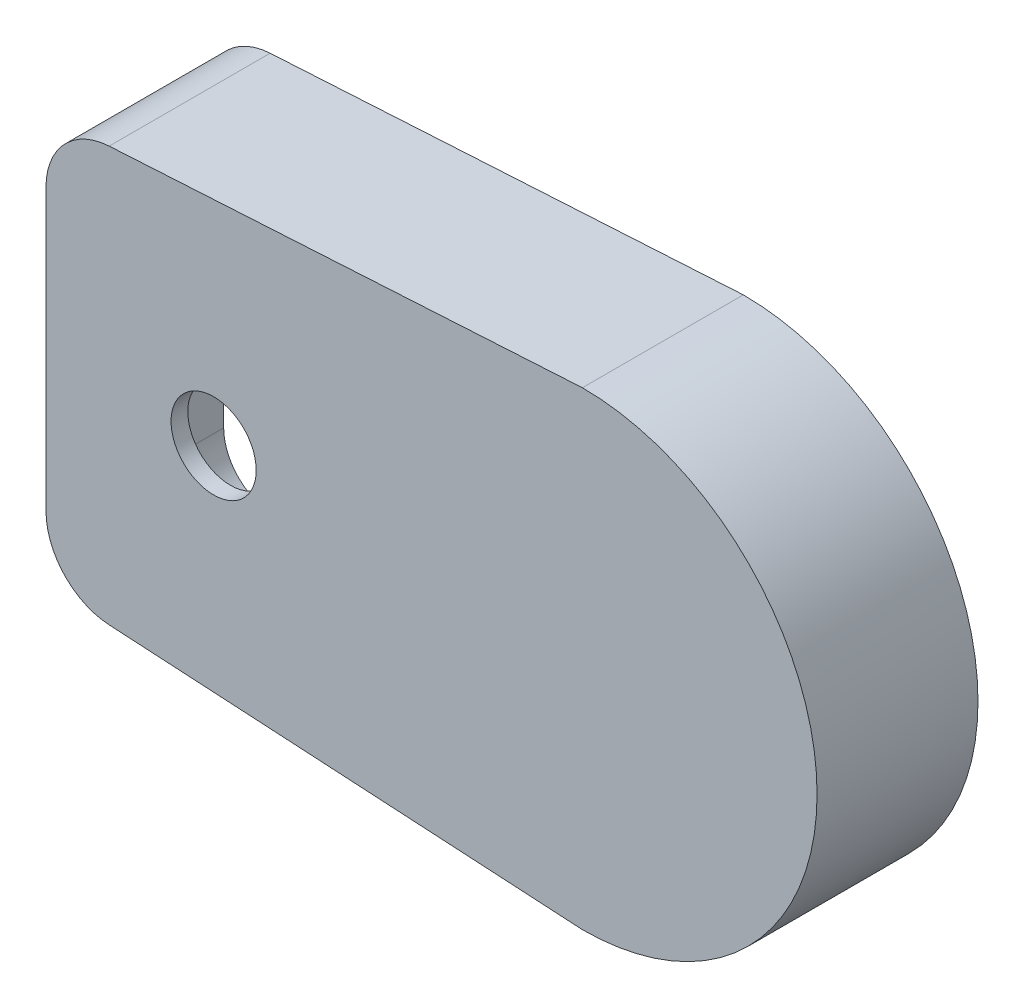
SolidWorks part; units mm, degrees
ref_plane "Front Plane" through (0, 0, 0) normal (0, 0, 1) x (1, 0, 0)
ref_plane "Top Plane" through (0, 0, 0) normal (0, 1, 0) x (1, 0, 0)
ref_plane "Right Plane" through (0, 0, 0) normal (1, 0, 0) x (0, 0, -1)
sketch "Sketch1" plane through (0, 0, 0) normal (0, 0, 1) x (1, 0, 0)
  line L0 (0, 0) -> (230, 0) construction
  line L1 (160, 52.3684) -> (160, -88.6842) construction
  line L2 (0, 41.8729) -> (0, -41.8729)
  line L3 (18.8457, 61.8395) -> (160, 70)
  line L4 (18.8457, -61.8395) -> (160, -70)
  arc A0 (160, -70) -> (160, 70) centre (160, 0) ccw
  arc A1 (18.8457, 61.8395) -> (0, 41.8729) centre (20, 41.8729) ccw
  arc A2 (18.8457, -61.8395) -> (0, -41.8729) centre (20, -41.8729) cw
  point P12 (0, 60.75)
  point P15 (0, -60.75)
  dimension "D4" = 20
  dimension "D5" = 20
  dimension "D1" = 230
  dimension "D2" = 70
  dimension "D3" = 121.5
extrude "Boss-Extrude1" add sketch "Sketch1" along normal mid plane 48 contours L3 A0 L4 A2 L2 A1
sketch "Sketch2" plane through (0, 0, -24) normal (0, 0, -1) x (-1, 0, 0)
  line L6 (-19.1343, 56.8479) -> (-160.1417, 64.9998)
  line L7 (-160.1417, -64.9998) -> (-19.1343, -56.8479)
  line L8 (-5, -41.8729) -> (-5, 41.8729)
  line L9 (-19.1343, 56.8479) -> (-160.1417, 64.9998)
  line L10 (-160.1417, -64.9998) -> (-19.1343, -56.8479)
  line L11 (-5, -41.8729) -> (-5, 41.8729)
  arc A6 (-5, 41.8729) -> (-19.1343, 56.8479) centre (-20, 41.8729) ccw
  arc A7 (-160.1417, 64.9998) -> (-160.1417, -64.9998) centre (-160, 0) ccw
  arc A8 (-19.1343, -56.8479) -> (-5, -41.8729) centre (-20, -41.8729) ccw
  arc A9 (-5, 41.8729) -> (-19.1343, 56.8479) centre (-20, 41.8729) ccw
  arc A10 (-160.1417, 64.9998) -> (-160.1417, -64.9998) centre (-160, 0) ccw
  arc A11 (-19.1343, -56.8479) -> (-5, -41.8729) centre (-20, -41.8729) ccw
  dimension "D1" = 5
extrude "Cut-Extrude1" cut sketch "Sketch2" against normal blind 43
sketch "Sketch7" plane through (0, 0, 24) normal (0, 0, 1) x (1, 0, 0)
  circle A0 centre (50, 0) radius 12.7
  dimension "D1" = 25.4
  dimension "D2" = 50
extrude "Cut-Extrude4" cut sketch "Sketch7" against normal blind 10
